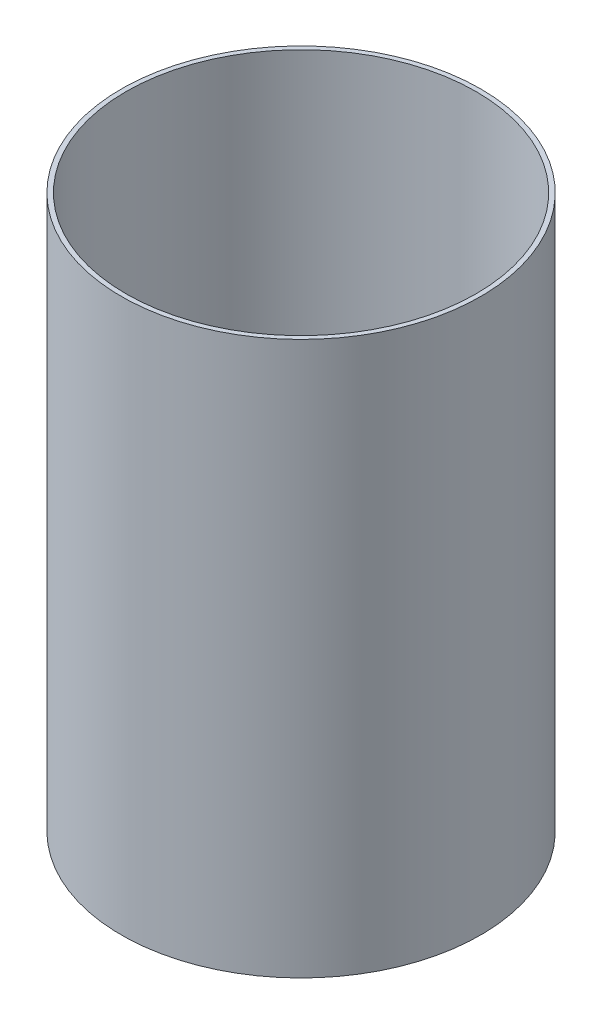
SolidWorks part; units mm, degrees
material "A-Glass Fiber"
ref_plane "Front Plane" through (0, 0, 0) normal (0, 0, 1) x (1, 0, 0)
ref_plane "Top Plane" through (0, 0, 0) normal (0, 1, 0) x (1, 0, 0)
ref_plane "Right Plane" through (0, 0, 0) normal (1, 0, 0) x (0, 0, -1)
sketch "Sketch1" plane through (0, 0, 0) normal (0, 1, 0) x (1, 0, 0)
  circle A0 centre (0, 0) radius 49.53
  circle A1 centre (0, 0) radius 48.26
  dimension "D1" = 99.06
  dimension "D2" = 96.52
extrude "Boss-Extrude1" add sketch "Sketch1" along normal blind 152.4 contours A1 | A0
equation "\"Length\"=6"
equation "\"D1@Boss-Extrude1\"=\"Length\""
